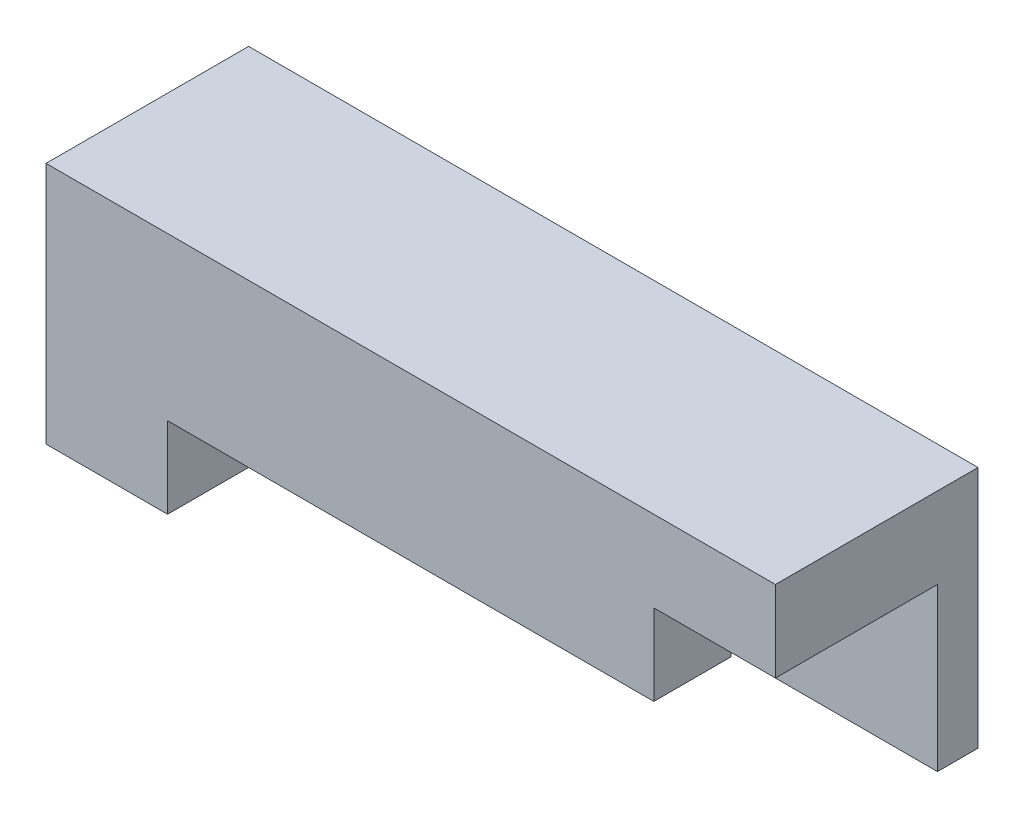
SolidWorks part; units mm, degrees
ref_plane "Front Plane" through (0, 0, 0) normal (0, 0, 1) x (1, 0, 0)
ref_plane "Top Plane" through (0, 0, 0) normal (0, 1, 0) x (1, 0, 0)
ref_plane "Right Plane" through (0, 0, 0) normal (1, 0, 0) x (0, 0, -1)
sketch "Sketch2" plane through (0, 0, 0) normal (0, 1, 0) x (1, 0, 0)
  line L1 (-9, -2.5) -> (9, -2.5)
  line L2 (-9, -2.5) -> (-9, 2.5)
  line L3 (-9, 2.5) -> (9, 2.5)
  line L4 (9, -2.5) -> (9, 2.5)
  line L5 (-9, -2.5) -> (9, 2.5) construction
  line L6 (-9, 2.5) -> (9, -2.5) construction
  point P0 (0, 0)
  dimension "D1" = 5
  dimension "D2" = 18
extrude "Boss-Extrude1" add sketch "Sketch2" along normal blind 6
sketch "Sketch3" plane through (9, 0, 0) normal (1, 0, 0) x (0, 0, -1)
  line L0 (2.5, 6) -> (2.5, 0) construction
  line L1 (-2.5, 0) -> (1.5, 0)
  line L3 (-0.6, 4) -> (1.5, 4)
  line L4 (1.5, 0) -> (1.5, 4)
  line L5 (-0.6, 4) -> (-0.6, 2)
  line L6 (-0.6, 2) -> (-2.5, 2)
  line L7 (-2.5, 0) -> (2.5, 0) construction
  line L8 (-2.5, 6) -> (-2.5, 0) construction
  line L9 (-2.5, 2) -> (-2.5, 0)
  line L11 (-2.5, 6) -> (2.5, 6) construction
  dimension "D1" = 2
  dimension "D3" = 1
  dimension "D4" = 2
  dimension "D5" = 2.1
extrude "Cut-Extrude1" cut sketch "Sketch3" against normal offset from surface (15 mm away) 3 up to face at (-9, 3, 0)
sketch "Sketch4" plane through (0, 0, 2.5) normal (0, 0, 1) x (1, 0, 0)
  line L0 (9, 6) -> (9, 2) construction
  line L1 (6, 4) -> (9, 4)
  line L2 (6, 4) -> (6, 2)
  line L3 (6, 2) -> (9, 2)
  line L4 (9, 4) -> (9, 2)
  line L5 (6, 4) -> (9, 2) construction
  line L6 (6, 2) -> (9, 4) construction
  line L7 (-6, 2) -> (9, 2) construction
  point P0 (7.5, 3)
  dimension "D1" = 2
  dimension "D2" = 3
extrude "Cut-Extrude2" cut sketch "Sketch4" against normal up to next
